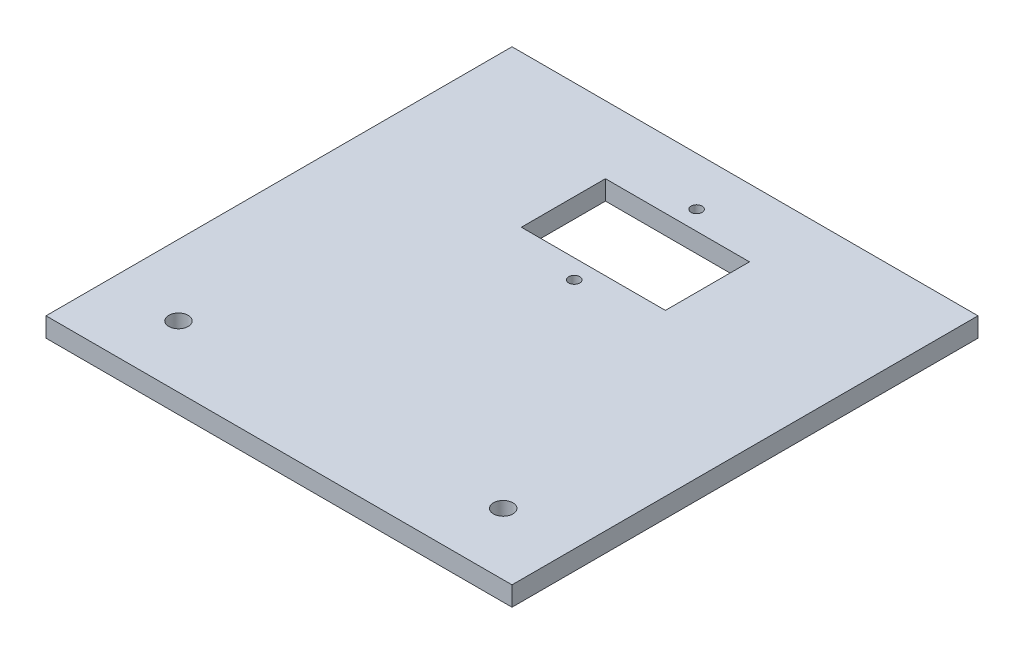
SolidWorks part; units mm, degrees
ref_plane "Front Plane" through (0, 0, 0) normal (0, 0, 1) x (1, 0, 0)
ref_plane "Top Plane" through (0, 0, 0) normal (0, 1, 0) x (1, 0, 0)
ref_plane "Right Plane" through (0, 0, 0) normal (1, 0, 0) x (0, 0, -1)
sketch "Sketch1" plane through (0, 0, 0) normal (0, 0, 1) x (1, 0, 0)
  line L0 (0, 3.175) -> (0, -3.175)
  line L1 (-76.2, 0) -> (76.2, 0) construction
  point P6 (0, 0)
  dimension "Width" = 152.4
  dimension "Thickness" = 6.35
sketch "Sketch2" plane through (0, 0, 0) normal (1, 0, 0) x (0, 0, -1)
  line L0 (76.2, 0) -> (-76.2, 0) construction
  point P4 (0, 0)
  dimension "Length" = 152.4
sketch "Sketch3" plane through (0, 0, 0) normal (0, 1, 0) x (1, 0, 0)
  line L5 (-76.2, -76.2) -> (76.2, -76.2)
  line L6 (-76.2, -76.2) -> (-76.2, 76.2)
  line L7 (-76.2, 76.2) -> (76.2, 76.2)
  line L8 (76.2, -76.2) -> (76.2, 76.2)
  line L9 (-76.2, -76.2) -> (76.2, 76.2) construction
  line L10 (-76.2, 76.2) -> (76.2, -76.2) construction
  point P0 (0, 0)
  point P1 (0, 0)
  dimension "D1" = 152.4
  dimension "D2" = 152.4
extrude "Boss-Extrude1" add sketch "Sketch3" along normal mid plane 6.35
sketch "Sketch4" plane through (0, 3.175, 0) normal (0, 1, 0) x (1, 0, 0)
  line L0 (0, 0) -> (0, 76.2) construction
  line L1 (23.55, 54.1111) -> (-23.55, 54.1111)
  line L2 (23.55, 54.1111) -> (23.55, 26.6111)
  line L3 (23.55, 26.6111) -> (-23.55, 26.6111)
  line L4 (-23.55, 54.1111) -> (-23.55, 26.6111)
  line L5 (23.55, 54.1111) -> (-23.55, 26.6111) construction
  line L6 (23.55, 26.6111) -> (-23.55, 54.1111) construction
  line L7 (76.2, 76.2) -> (-76.2, 76.2) construction
  line L8 (0, 40.3611) -> (-23.55, 40.3611) construction
  circle A0 centre (0, 60.3611) radius 1.8
  circle A1 centre (0, 20.3611) radius 1.8
  point P0 (0, 40.3611)
  dimension "D3" = 3.6
  dimension "D1" = 27.5
  dimension "D2" = 47.1
  dimension "D4" = 6.25
extrude "Cut-Extrude1" cut sketch "Sketch4" against normal blind 10 contours L2 L1 L4 L3 | A0 | A1
sketch "Sketch5" plane through (0, 0, 0) normal (0, 1, 0) x (1, 0, 0)
  line L0 (-24.9998, -55.981) -> (25.0001, -55.981) construction
  line L3 (0, -75.8295) -> (0, -35.8295) construction
  line L4 (0, 0) -> (0, -76.2) construction
  line L5 (-76.2, -76.2) -> (76.2, -76.2) construction
  circle A0 centre (-53.0969, -55.981) radius 3.175
  circle A1 centre (53.0969, -55.981) radius 3.175
  point P2 (-24.131, -55.8708)
  point P4 (-53.0969, -55.981)
  dimension "D1" = 6.35
extrude "Cut-Extrude2" cut sketch "Sketch5" against normal mid plane 10
equation "\"D1@Sketch3\"=\"Width@Sketch1\""
equation "\"D2@Sketch3\"=\"Length@Sketch2\""
equation "\"D1@Boss-Extrude1\"=\"Thickness@Sketch1\""
